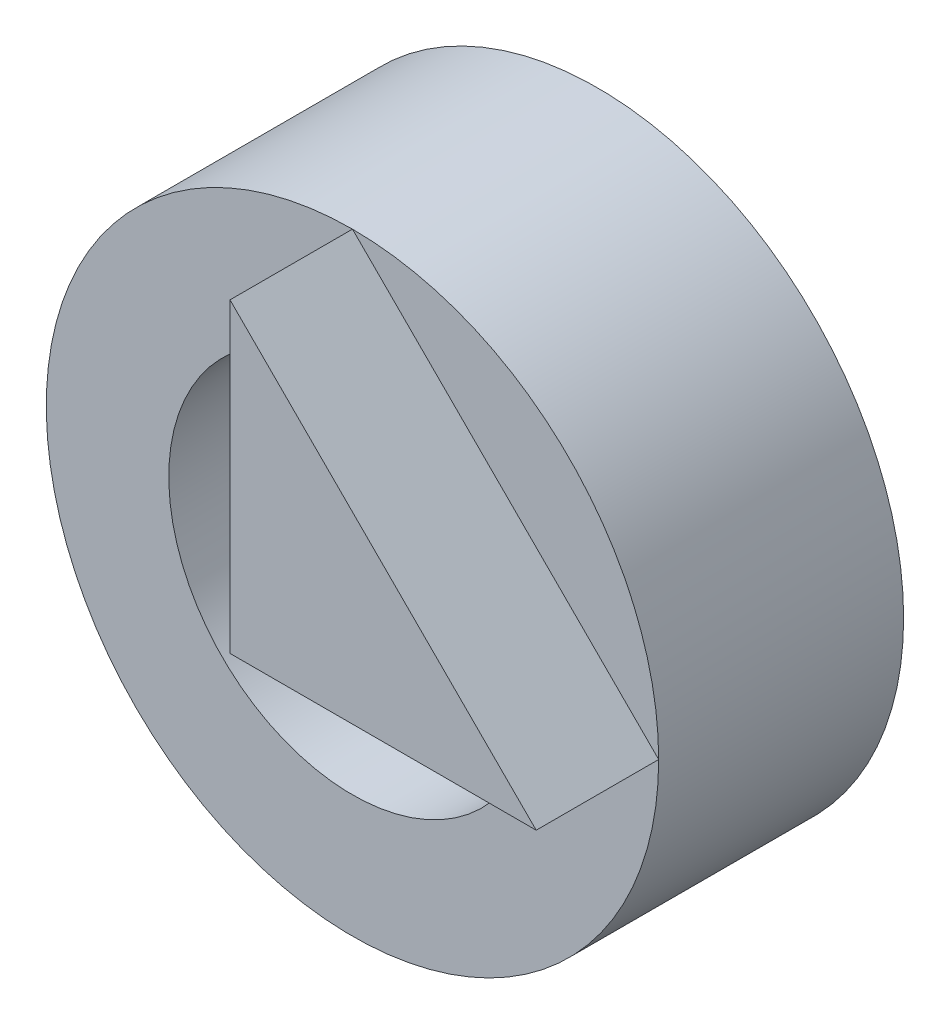
SolidWorks part; units mm, degrees
ref_plane "Plan de face" through (0, 0, 0) normal (0, 0, 1) x (1, 0, 0)
ref_plane "Plan de dessus" through (0, 0, 0) normal (0, 1, 0) x (1, 0, 0)
ref_plane "Plan de droite" through (0, 0, 0) normal (1, 0, 0) x (0, 0, -1)
sketch "Esquisse1" plane through (0, 0, 0) normal (0, 0, 1) x (1, 0, 0)
  circle A0 centre (0, 0) radius 1.5
  circle A1 centre (0, 0) radius 2.5
  dimension "D1" = 3
  dimension "D2" = 1
extrude "Boss.-Extru.1" add sketch "Esquisse1" along normal blind 2
sketch "Esquisse2" plane through (0, 0, 2) normal (0, 0, 1) x (1, 0, 0)
  line L0 (0, 0) -> (0, 2.5)
  line L1 (0, 2.5) -> (2.5, 0)
  line L2 (2.5, 0) -> (0, 0)
  circle A0 centre (0, 0) radius 2.5 construction
extrude "Boss.-Extru.2" add sketch "Esquisse2" along normal blind 1
